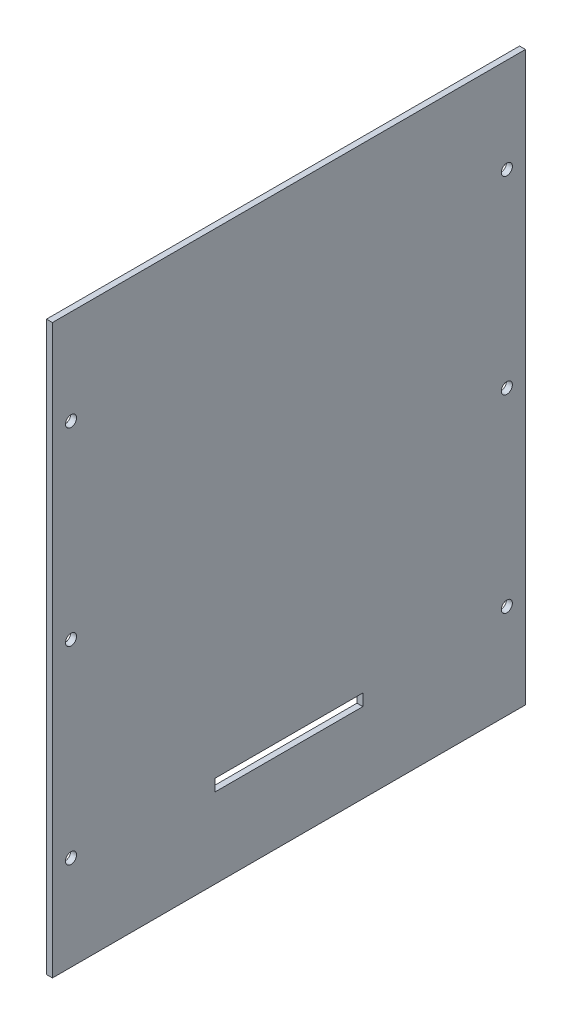
SolidWorks part; units mm, degrees
material "6061-T6 (SS)"
ref_plane "Front Plane" through (0, 0, 0) normal (0, 0, 1) x (1, 0, 0)
ref_plane "Top Plane" through (0, 0, 0) normal (0, 1, 0) x (1, 0, 0)
ref_plane "Right Plane" through (0, 0, 0) normal (1, 0, 0) x (0, 0, -1)
sketch "Sketch1" plane through (0, 0, 0) normal (0, 1, 0) x (1, 0, 0)
  line L1 (-1.5875, -127) -> (1.5875, -127)
  line L2 (-1.5875, -127) -> (-1.5875, 127)
  line L3 (-1.5875, 127) -> (1.5875, 127)
  line L4 (1.5875, -127) -> (1.5875, 127)
  line L5 (-1.5875, -127) -> (1.5875, 127) construction
  line L6 (-1.5875, 127) -> (1.5875, -127) construction
  point P0 (0, 0)
  dimension "D1" = 3.175
  dimension "D2" = 254
extrude "Boss-Extrude1" add sketch "Sketch1" along normal mid plane 304.8
sketch "Sketch2" plane through (1.5875, 0, 0) normal (1, 0, 0) x (0, 0, -1)
  line L0 (-169.5346, 0) -> (169.5346, 0) construction
  line L1 (0, 166.6389) -> (0, -166.6389) construction
  line L2 (-127, -152.4) -> (127, -152.4) construction
  line L3 (-39.6875, -109.5375) -> (39.6875, -109.5375)
  line L4 (-39.6875, -109.5375) -> (-39.6875, -103.1875)
  line L5 (-39.6875, -103.1875) -> (39.6875, -103.1875)
  line L6 (39.6875, -109.5375) -> (39.6875, -103.1875)
  line L7 (-39.6875, -109.5375) -> (39.6875, -103.1875) construction
  line L8 (-39.6875, -103.1875) -> (39.6875, -109.5375) construction
  point P0 (0, -106.3625)
  point P4 (0, 0)
  point P8 (0, 0)
  dimension "D1" = 46.0375
  dimension "D2" = 6.35
  dimension "D3" = 79.375
extrude "Cut-Extrude1" cut sketch "Sketch2" against normal blind 3.175
sketch "Sketch3" plane through (1.5875, 0, 0) normal (1, 0, 0) x (0, 0, -1)
  line L0 (-243.3137, 0) -> (243.3137, 0) construction
  line L1 (0, -189.0308) -> (0, 189.0308) construction
  line L2 (127, 152.4) -> (127, -152.4) construction
  circle A0 centre (117, 0) radius 2.9769
  circle A1 centre (117, 101.6) radius 2.9769
  circle A2 centre (117, -101.6) radius 2.9769
  circle A3 centre (-117, -101.6) radius 2.9769
  circle A4 centre (-117, 0) radius 2.9769
  circle A5 centre (-117, 101.6) radius 2.9769
  point P4 (0, 0)
  point P8 (0, 0)
  dimension "D2" = 5.9538
  dimension "D1" = 10
  dimension "D3" = 2
extrude "Cut-Extrude2" cut sketch "Sketch3" against normal blind 3.175
